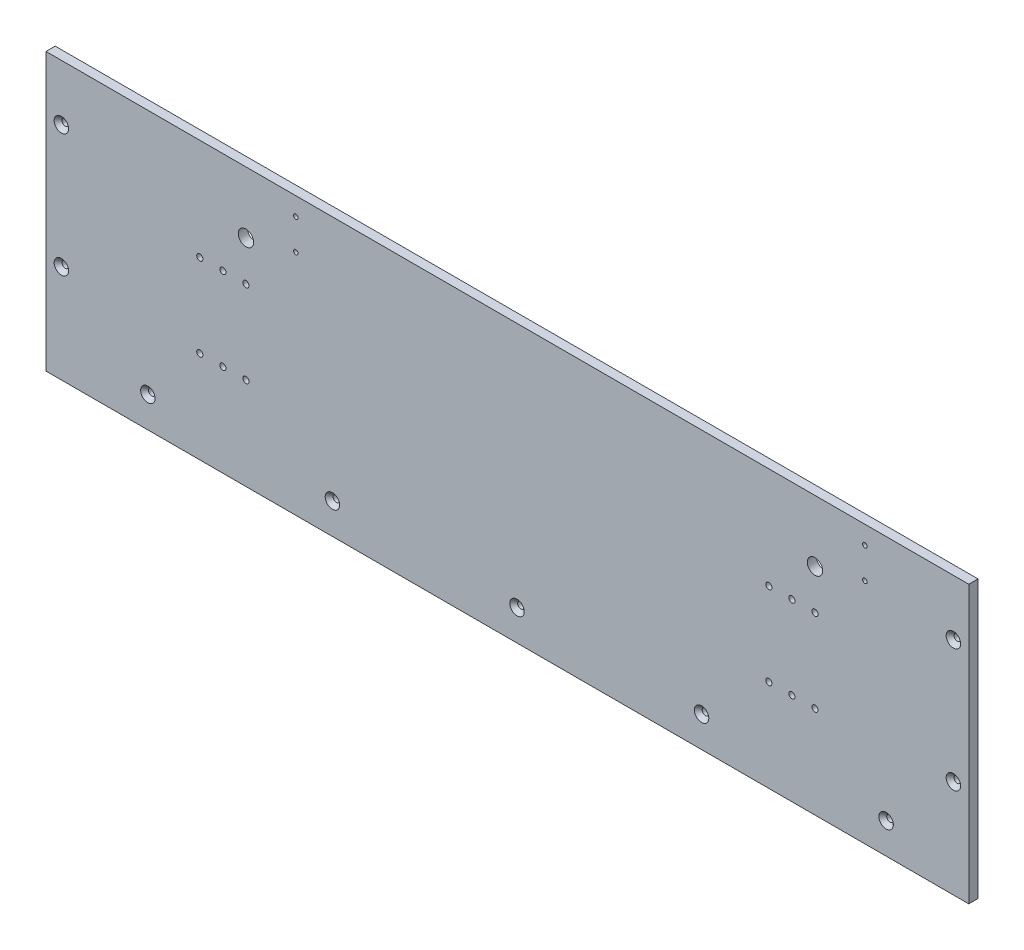
SolidWorks part; units mm, degrees
ref_plane "Płaszczyzna przednia" through (0, 0, 0) normal (0, 0, 1) x (1, 0, 0)
ref_plane "Płaszczyzna górna" through (0, 0, 0) normal (0, 1, 0) x (1, 0, 0)
ref_plane "Płaszczyzna prawa" through (0, 0, 0) normal (1, 0, 0) x (0, 0, -1)
sketch "Sketch1" plane through (0, 0, 0) normal (0, 0, 1) x (1, 0, 0)
  line L1 (0, 0) -> (600, 0)
  line L2 (0, 0) -> (0, 180)
  line L3 (0, 180) -> (600, 180)
  line L4 (600, 0) -> (600, 180)
  line L5 (0, 0) -> (600, 180) construction
  line L6 (0, 180) -> (600, 0) construction
  point P4 (300, 90)
  dimension "D1" = 600
  dimension "D2" = 180
extrude "Boss-Extrude1" add sketch "Sketch1" along normal blind 6
hole_wizard "CSK for M4 Flat Head Machine Screw1" positions "Sketch2" profile "Sketch3" countersink size "M4" standard "ANSI Metric" end condition through all
sketch "Sketch2" plane through (0, 0, 6) normal (0, 0, 1) x (1, 0, 0)
  line L0 (600, 0) -> (600, 180) construction
  line L1 (0, 0) -> (600, 0) construction
  point P0 (546.25, 20)
  point P2 (590, 63.75)
  point P13 (426.25, 20)
  point P14 (306.25, 20)
  point P15 (186.25, 20)
  point P16 (66.25, 20)
  point P21 (10, 63.75)
  point P28 (590, 143.75)
  point P29 (10, 143.75)
  dimension "D1" = 53.75
  dimension "D2" = 63.75
  dimension "D3" = 10
  dimension "D4" = 20
  dimension "D5" = 5
  dimension "D6" = 2
  dimension "D7" = 2
sketch "Sketch3" plane through (546.25, 20, 6) normal (1, 0, 0) x (0, -1, 0)
  line L0 (0, 0) -> (0, 6)
  line L1 (0, 6) -> (2.15, 6)
  line L2 (2.15, 6) -> (2.15, 2.55)
  line L3 (2.15, 2.55) -> (4.7, 0)
  line L5 (4.7, 0) -> (0, 0)
  line L6 (-2.15, 2.55) -> (-4.7, 0) construction
  line L11 (0, -6.35) -> (0, 107.95) construction
  dimension "Thru Hole Dia." = 4.3
  dimension "Thru Hole Depth" = 6
  dimension "Near C'Sink Dia." = 9.4
  dimension "Near C'Sink Angle" = 90
hole_wizard "Ø4.0mm Dowel Hole1" positions "Sketch4" profile "Sketch5" hole size "Ø4.0" standard "ANSI Metric" end condition through all
sketch "Sketch4" plane through (0, 0, 6) normal (0, 0, 1) x (1, 0, 0)
  line L0 (600, 0) -> (600, 180) construction
  line L1 (0, 0) -> (600, 0) construction
  line L2 (300, 0) -> (300, 180) construction
  line L3 (600, 180) -> (0, 180) construction
  point P0 (500, 60)
  point P9 (485, 60)
  point P10 (470, 60)
  point P11 (485, 114)
  point P12 (470, 114)
  point P13 (500, 114)
  point P24 (130, 114)
  point P25 (115, 114)
  point P26 (100, 114)
  point P27 (130, 60)
  point P28 (115, 60)
  point P29 (100, 60)
  dimension "D3" = 100
  dimension "D4" = 60
  dimension "D1" = 3
  dimension "D2" = 2
sketch "Sketch5" plane through (500, 60, 6) normal (1, 0, 0) x (0, -1, 0)
  line L0 (0, 0) -> (0, 6)
  line L1 (0, 6) -> (2, 6)
  line L2 (2, 6) -> (2, 0)
  line L5 (2, 0) -> (0, 0)
  line L11 (0, -6.35) -> (0, 107.95) construction
  dimension "Thru Hole Dia." = 4
  dimension "Thru Hole Depth" = 6
hole_wizard "Ø3.0mm Dowel Hole1" positions "Sketch6" profile "Sketch7" hole size "Ø3.0" standard "ANSI Metric" end condition through all
sketch "Sketch6" plane through (0, 0, 6) normal (0, 0, 1) x (1, 0, 0)
  line L0 (0, 0) -> (600, 0) construction
  line L2 (600, 0) -> (600, 180) construction
  line L3 (300, 0) -> (300, 181.4009) construction
  line L5 (600, 0) -> (600, 552) construction
  line L6 (0, 180) -> (0, 0) construction
  point P0 (532.43, 148.2)
  point P2 (532.43, 168.2)
  point P23 (162.43, 148.2)
  point P25 (162.43, 168.2)
  dimension "D1" = 20
  dimension "D2" = 148.2
  dimension "D3" = 67.57
  dimension "D4" = 300
  dimension "D5" = 162.43
  dimension "D6" = 20
  dimension "D7" = 148.2
sketch "Sketch7" plane through (532.43, 148.2, 6) normal (1, 0, 0) x (0, -1, 0)
  line L0 (0, 0) -> (0, 6)
  line L1 (0, 6) -> (1.5, 6)
  line L2 (1.5, 6) -> (1.5, 0)
  line L5 (1.5, 0) -> (0, 0)
  line L11 (0, -6.35) -> (0, 107.95) construction
  dimension "Thru Hole Dia." = 3
  dimension "Thru Hole Depth" = 6
sketch "Sketch8" plane through (0, 0, 6) normal (0, 0, 1) x (1, 0, 0)
  line L0 (600, 0) -> (600, 180) construction
  line L1 (0, 0) -> (600, 0) construction
  line L2 (0, 180) -> (0, 0) construction
  circle A0 centre (500, 140) radius 5
  circle A1 centre (130, 140) radius 5
  dimension "D1" = 10
  dimension "D2" = 100
  dimension "D3" = 140
  dimension "D4" = 10
  dimension "D5" = 140
  dimension "130" = 130
extrude "Cut-Extrude1" cut sketch "Sketch8" against normal blind 10
